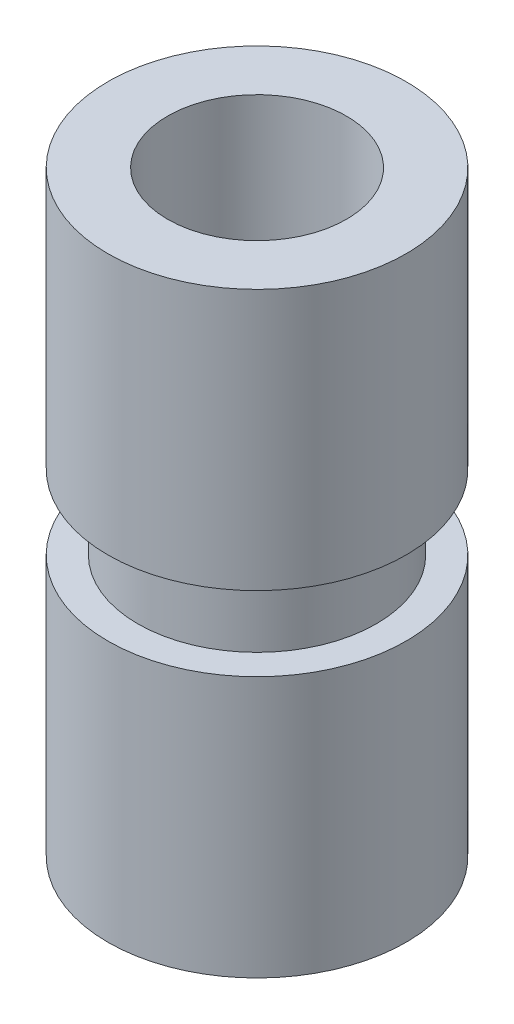
SolidWorks part; units mm, degrees
ref_plane "Front Plane" through (0, 0, 0) normal (0, 0, 1) x (1, 0, 0)
ref_plane "Top Plane" through (0, 0, 0) normal (0, 1, 0) x (1, 0, 0)
ref_plane "Right Plane" through (0, 0, 0) normal (1, 0, 0) x (0, 0, -1)
sketch "Sketch2" plane through (0, 0, 0) normal (0, 1, 0) x (1, 0, 0)
  circle A0 centre (0, 0) radius 1
extrude "Boss-Extrude1" add sketch "Sketch2" along normal blind 4
ref_plane "Plane1" through (0, 2, 0) normal (0, 1, 0) x (1, 0, 0)
sketch "Sketch4" plane through (0, 2, 0) normal (0, 1, 0) x (1, 0, 0)
  circle A0 centre (0, 0) radius 0.8
  dimension "D1" = 1.6
extrude "Cut-Extrude1" cut sketch "Sketch4" against normal blind 0.25 and the other way blind 0.25 flip side to cut
sketch "Sketch5" plane through (0, 4, 0) normal (0, 1, 0) x (1, 0, 0)
  circle A0 centre (0, 0) radius 0.6
  dimension "D1" = 1.2
extrude "Cut-Extrude2" cut sketch "Sketch5" against normal blind 7.5
